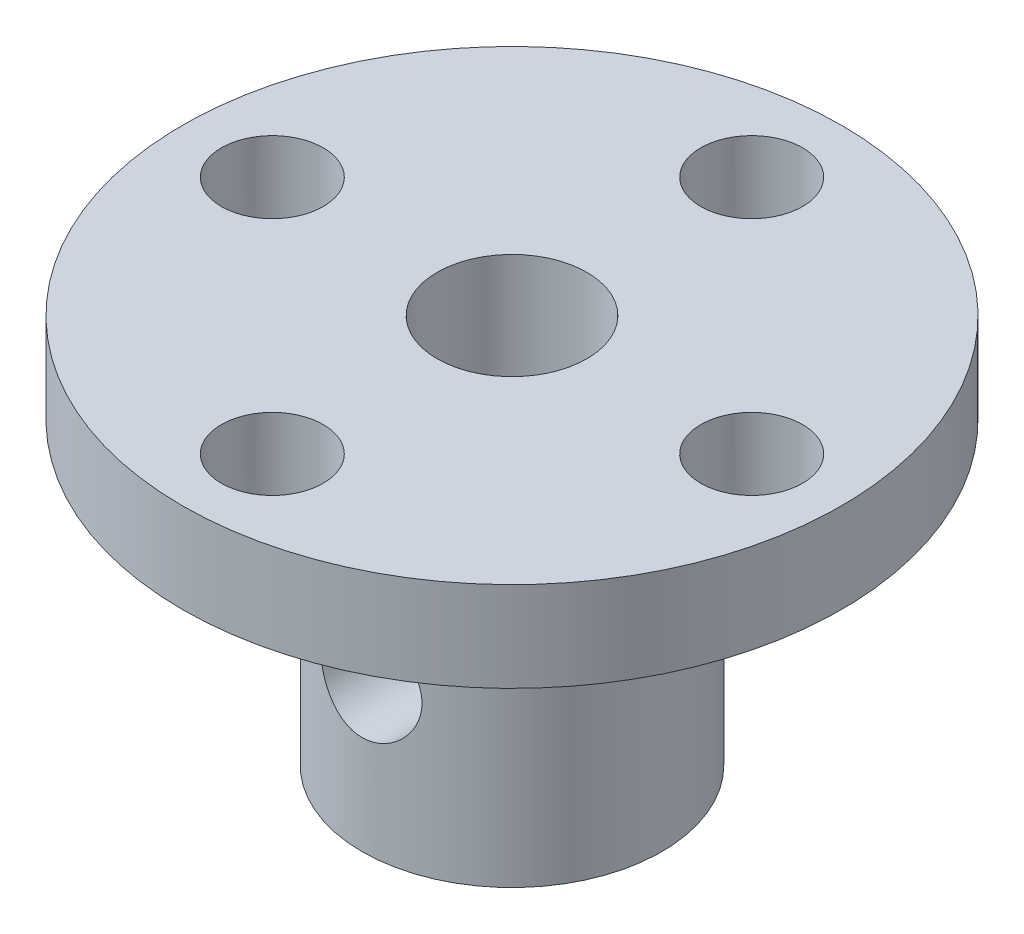
SolidWorks part; units mm, degrees
ref_plane "前视基准面" through (0, 0, 0) normal (0, 0, 1) x (1, 0, 0)
ref_plane "上视基准面" through (0, 0, 0) normal (0, 1, 0) x (1, 0, 0)
ref_plane "右视基准面" through (0, 0, 0) normal (1, 0, 0) x (0, 0, -1)
other "Configuration Table"
sketch "草图1" plane through (0, 0, 0) normal (0, 0, 1) x (1, 0, 0)
  line L0 (0, 0) -> (0, -14.1868) construction
  line L1 (-2.5, 0) -> (-11, 0)
  line L2 (-11, 0) -> (-11, -3)
  line L3 (-11, -3) -> (-5, -3)
  line L4 (-5, -3) -> (-5, -13)
  line L5 (-5, -13) -> (-2.5, -13)
  line L6 (-2.5, -13) -> (-2.5, 0)
  point P10 (-1.5474, 0)
  dimension "D1" = 10
  dimension "D2" = 22
  dimension "D3" = 5
  dimension "D4" = 3
  dimension "D5" = 10
revolve "旋转1" add sketch "草图1" angle 360 about L0
sketch "草图2" plane through (0, 0, 0) normal (0, 1, 0) x (1, 0, 0)
  line L0 (0, 0) -> (0, 8) construction
  circle A0 centre (0, 8) radius 1.7
  circle A1 centre (8, 0) radius 1.7
  circle A2 centre (0, -8) radius 1.7
  circle A3 centre (-8, 0) radius 1.7
  point P13 (0, 0)
  dimension "D1" = 3.4
  dimension "D2" = 8
  dimension "D3" = 4
extrude "切除-拉伸1" cut sketch "草图2" against normal blind 10
sketch "草图3" plane through (0, 0, 0) normal (0, 0, 1) x (1, 0, 0)
  line L0 (0, 0) -> (0, -16.5829) construction
  circle A0 centre (0, -8) radius 1.7
  dimension "D1" = 3.4
  dimension "D2" = 8
extrude "切除-拉伸2" cut sketch "草图3" against normal through all both and the other way through all
